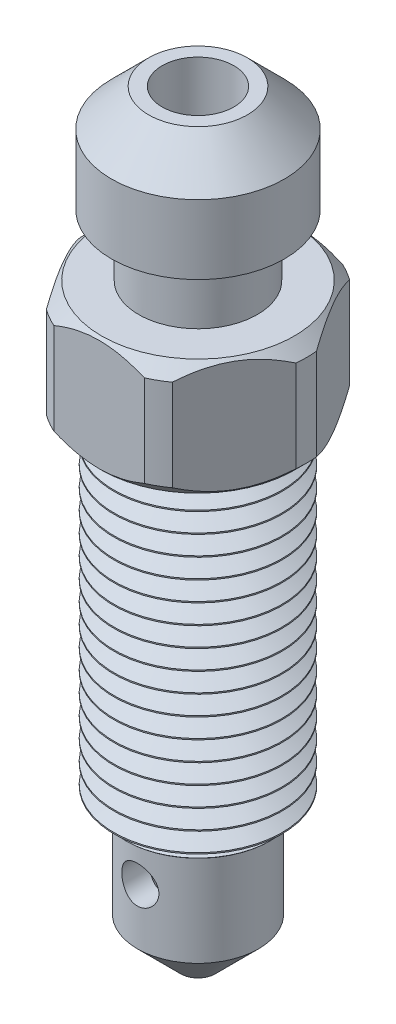
SolidWorks part; units mm, degrees
ref_plane "Front Plane" through (0, 0, 0) normal (0, 0, 1) x (1, 0, 0)
ref_plane "Top Plane" through (0, 0, 0) normal (0, 1, 0) x (1, 0, 0)
ref_plane "Right Plane" through (0, 0, 0) normal (1, 0, 0) x (0, 0, -1)
sketch "Sketch1" plane through (0, 0, 0) normal (0, 0, 1) x (1, 0, 0)
  line L0 (0, 0) -> (-0.7, 0)
  line L1 (-0.7, 0) -> (-2.45, 1.75)
  line L2 (-2.45, 1.75) -> (-2.45, 5.75)
  line L3 (-2.45, 5.75) -> (-3.4, 5.75)
  line L4 (-3.4, 5.75) -> (-3.4, 19.25)
  line L5 (-3.4, 19.25) -> (-4.4, 19.25)
  line L6 (-4.4, 19.25) -> (-4.4, 23.95)
  line L7 (-4.4, 23.95) -> (-2.4, 23.95)
  line L8 (-2.4, 23.95) -> (-2.4, 26.45)
  line L9 (-2.4, 26.45) -> (-3.5, 26.45)
  line L10 (-3.5, 26.45) -> (-3.5, 29.25)
  line L11 (-3.5, 29.25) -> (-2, 30.75)
  line L12 (-2, 30.75) -> (-1.45, 30.75)
  line L13 (-1.45, 30.75) -> (-1.45, 2)
  line L14 (-1.45, 2) -> (0, 2)
  line L15 (0, 2) -> (0, 0)
  line L16 (0, 1.983) -> (0, 25.3115) construction
  dimension "D1" = 0.7
  dimension "D2" = 4.9
  dimension "D3" = 45
  dimension "D4" = 4
  dimension "D5" = 6.8
  dimension "D6" = 13.5
  dimension "D7" = 8.8
  dimension "D8" = 4.7
  dimension "D9" = 4.8
  dimension "D10" = 2.5
  dimension "D11" = 4.3
  dimension "D12" = 45
  dimension "D13" = 7
  dimension "D14" = 4
  dimension "D15" = 2.9
  dimension "D16" = 2
revolve "Revolve1" add sketch "Sketch1" angle 360 about L16
chamfer "Chamfer1" distance 0.5 angle 45 2 edges at (0, 19.25, -4.4) (0, 23.95, -4.4)
fillet "Fillet1" radius 0.5 1 edges at (0, 26.45, -2.4)
sketch "Sketch2" plane through (0, 0, 0) normal (0, 0, 1) x (1, 0, 0)
  line L0 (0, 0) -> (0, 4) construction
  line L1 (-0.7, 0) -> (0.7, 0) construction
  circle A0 centre (0, 4) radius 0.75
  dimension "D1" = 1.5
  dimension "D2" = 4
extrude "Cut-Extrude1" cut sketch "Sketch2" against normal through all both and the other way through all
sketch "Sketch3" plane through (0, 23.95, 0) normal (0, 1, 0) x (1, 0, 0)
  line L1 (4.6188, 0) -> (2.3094, 4)
  line L2 (2.3094, 4) -> (-2.3094, 4)
  line L3 (-2.3094, 4) -> (-4.6188, 0)
  line L4 (-4.6188, 0) -> (-2.3094, -4)
  line L5 (-2.3094, -4) -> (2.3094, -4)
  line L6 (2.3094, -4) -> (4.6188, 0)
  circle A0 centre (0, 0) radius 4 construction
  dimension "D1" = 8
extrude "Cut-Extrude2" cut sketch "Sketch3" against normal blind 5 flip side to cut
chamfer "Chamfer2" distance 0.5 angle 45 1 edges at (0, 5.75, -3.4)
sketch "Sketch4" plane through (0, 0, 0) normal (0, 0, 1) x (1, 0, 0)
  line L0 (0, 0) -> (0, 31.7196) construction
  line L1 (3.4, 5.5) -> (3.4, 6.25)
  line L2 (3.4, 6.25) -> (2.7505, 5.875)
  line L3 (2.7505, 5.875) -> (3.4, 5.5)
  line L5 (3.4, 6.25) -> (3.4, 19.25) construction
  line L6 (3.4, 7.05) -> (2.7505, 6.675)
  line L7 (3.4, 6.3) -> (3.4, 7.05)
  line L8 (2.7505, 6.675) -> (3.4, 6.3)
  line L9 (3.4, 7.85) -> (2.7505, 7.475)
  line L10 (3.4, 7.1) -> (3.4, 7.85)
  line L11 (2.7505, 7.475) -> (3.4, 7.1)
  line L12 (3.4, 8.65) -> (2.7505, 8.275)
  line L13 (3.4, 7.9) -> (3.4, 8.65)
  line L14 (2.7505, 8.275) -> (3.4, 7.9)
  line L15 (3.4, 9.45) -> (2.7505, 9.075)
  line L16 (3.4, 8.7) -> (3.4, 9.45)
  line L17 (2.7505, 9.075) -> (3.4, 8.7)
  line L18 (3.4, 10.25) -> (2.7505, 9.875)
  line L19 (3.4, 9.5) -> (3.4, 10.25)
  line L20 (2.7505, 9.875) -> (3.4, 9.5)
  line L21 (3.4, 11.05) -> (2.7505, 10.675)
  line L22 (3.4, 10.3) -> (3.4, 11.05)
  line L23 (2.7505, 10.675) -> (3.4, 10.3)
  line L24 (3.4, 11.85) -> (2.7505, 11.475)
  line L25 (3.4, 11.1) -> (3.4, 11.85)
  line L26 (2.7505, 11.475) -> (3.4, 11.1)
  line L27 (3.4, 12.65) -> (2.7505, 12.275)
  line L28 (3.4, 11.9) -> (3.4, 12.65)
  line L29 (2.7505, 12.275) -> (3.4, 11.9)
  line L30 (3.4, 13.45) -> (2.7505, 13.075)
  line L31 (3.4, 12.7) -> (3.4, 13.45)
  line L32 (2.7505, 13.075) -> (3.4, 12.7)
  line L33 (3.4, 14.25) -> (2.7505, 13.875)
  line L34 (3.4, 13.5) -> (3.4, 14.25)
  line L35 (2.7505, 13.875) -> (3.4, 13.5)
  line L36 (3.4, 15.05) -> (2.7505, 14.675)
  line L37 (3.4, 14.3) -> (3.4, 15.05)
  line L38 (2.7505, 14.675) -> (3.4, 14.3)
  line L39 (3.4, 15.85) -> (2.7505, 15.475)
  line L40 (3.4, 15.1) -> (3.4, 15.85)
  line L41 (2.7505, 15.475) -> (3.4, 15.1)
  line L42 (3.4, 16.65) -> (2.7505, 16.275)
  line L43 (3.4, 15.9) -> (3.4, 16.65)
  line L44 (2.7505, 16.275) -> (3.4, 15.9)
  line L45 (3.4, 17.45) -> (2.7505, 17.075)
  line L46 (3.4, 16.7) -> (3.4, 17.45)
  line L47 (2.7505, 17.075) -> (3.4, 16.7)
  line L48 (3.4, 18.25) -> (2.7505, 17.875)
  line L49 (3.4, 17.5) -> (3.4, 18.25)
  line L50 (2.7505, 17.875) -> (3.4, 17.5)
  line L51 (3.4, 19.05) -> (2.7505, 18.675)
  line L52 (3.4, 18.3) -> (3.4, 19.05)
  line L53 (2.7505, 18.675) -> (3.4, 18.3)
  dimension "D1" = 0.75
  dimension "D2" = 17
revolve "Cut-Revolve1" cut sketch "Sketch4" angle 360 about L0
